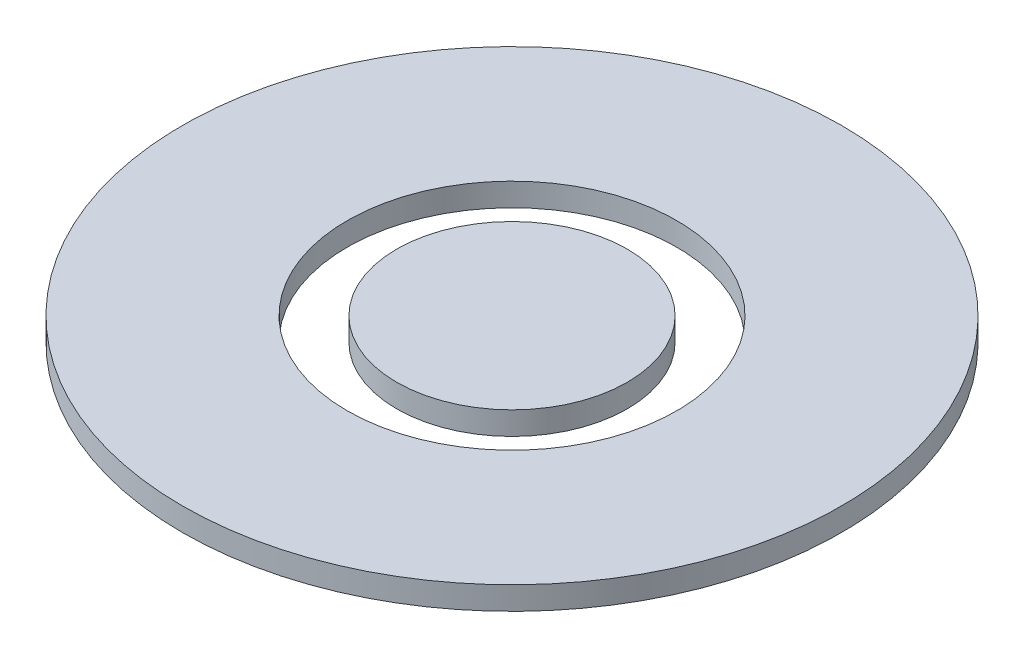
SolidWorks part; units mm, degrees
ref_plane "Front Plane" through (0, 0, 0) normal (0, 0, 1) x (1, 0, 0)
ref_plane "Top Plane" through (0, 0, 0) normal (0, 1, 0) x (1, 0, 0)
ref_plane "Right Plane" through (0, 0, 0) normal (1, 0, 0) x (0, 0, -1)
sketch "Sketch1" plane through (0, 0, 0) normal (0, 1, 0) x (1, 0, 0)
  circle A0 centre (0, 0) radius 10
  circle A1 centre (0, 0) radius 3.5
  circle A2 centre (0, 0) radius 5
  dimension "D1" = 20
  dimension "D2" = 7
  dimension "D3" = 10
extrude "Boss-Extrude1" add sketch "Sketch1" along normal blind 0.7 contours A2 | A0
sketch "Sketch2" plane through (0, 0, 0) normal (0, 1, 0) x (1, 0, 0)
  circle A0 centre (0, 0) radius 3.5
  dimension "D1" = 7
extrude "Boss-Extrude2" add sketch "Sketch2" along normal blind 0.7 separate body
